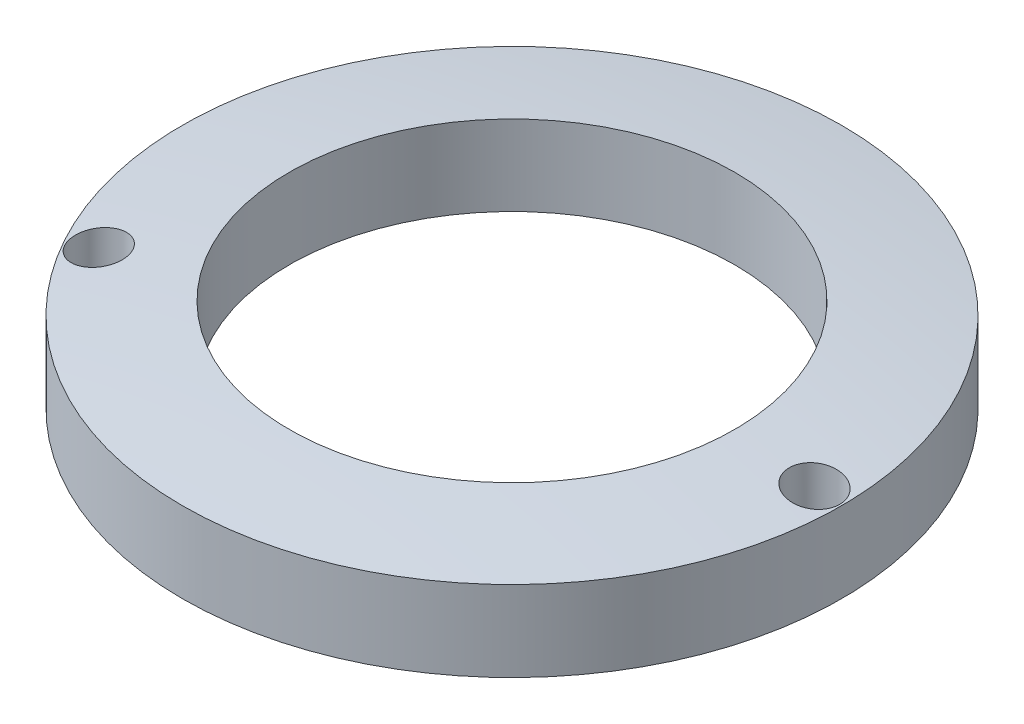
SolidWorks part; units mm, degrees
ref_plane "Front" through (0, 0, 0) normal (0, 0, 1) x (1, 0, 0)
ref_plane "Top" through (0, 0, 0) normal (0, 1, 0) x (1, 0, 0)
ref_plane "Right" through (0, 0, 0) normal (1, 0, 0) x (0, 0, -1)
sketch "Sketch1" plane through (0, 0, 0) normal (0, 0, 1) x (1, 0, 0)
  line L0 (26.51, 277.4865) -> (26.51, 268.9466)
  line L1 (0, 0) -> (26.51, 0) construction
  line L2 (0, 0) -> (0, 322.5334) construction
  line L3 (0, 322.5334) -> (26.51, 322.5334) construction
  line L4 (26.51, 0) -> (26.51, 322.5334) construction
  line L5 (0, 0) -> (39.22, 0) construction
  line L6 (0, 0) -> (0, 322.5334) construction
  line L7 (0, 322.5334) -> (39.22, 322.5334) construction
  line L8 (39.22, 0) -> (39.22, 322.5334) construction
  line L9 (39.22, 275.9771) -> (39.22, 267.389)
  line L10 (26.51, 278.4865) -> (26.51, 277.4865)
  line L11 (39.22, 276.9771) -> (39.22, 275.9771)
  arc A0 (39.22, 275.9771) -> (26.51, 277.4865) centre (0, 0) ccw construction
  arc A1 (39.22, 267.389) -> (26.51, 268.9466) centre (0, 0) ccw
  arc A2 (39.22, 276.9771) -> (26.51, 278.4865) centre (0, 1) ccw
  dimension "D1" = 557.5
  dimension "D2" = 540.5
  dimension "D5" = 278.75
  dimension "D3" = 26.51
  dimension "D4" = 39.22
  dimension "D6" = 1
revolve "Revolve1" add sketch "Sketch1" angle 360 about L2
sketch "Sketch2" plane through (0, 0, 0) normal (0, 1, 0) x (1, 0, 0)
  line L0 (0, 0) -> (36, 0) construction
  line L1 (0, 0) -> (-31.1769, -18) construction
  circle A0 centre (0, 0) radius 36 construction
  circle A1 centre (-31.1769, -18) radius 3
  circle A2 centre (36, 0) radius 3
  dimension "D2" = 6
  dimension "D3" = 6
  dimension "D4" = 72
  dimension "D1" = 150
extrude "Cut-Extrude3" cut sketch "Sketch2" along normal through all
sketch "Sketch3" plane through (0, 0, 0) normal (0, 0, 1) x (1, 0, 0)
  line L0 (-39.22, 267.389) -> (39.22, 267.389) construction
  line L1 (39.22, 267.389) -> (39.22, 265.389) construction
  line L2 (39.22, 265.389) -> (-39.22, 267.389) construction
  line L3 (0, 266.389) -> (0.5528, 288.0709) construction
  dimension "D1" = 2
